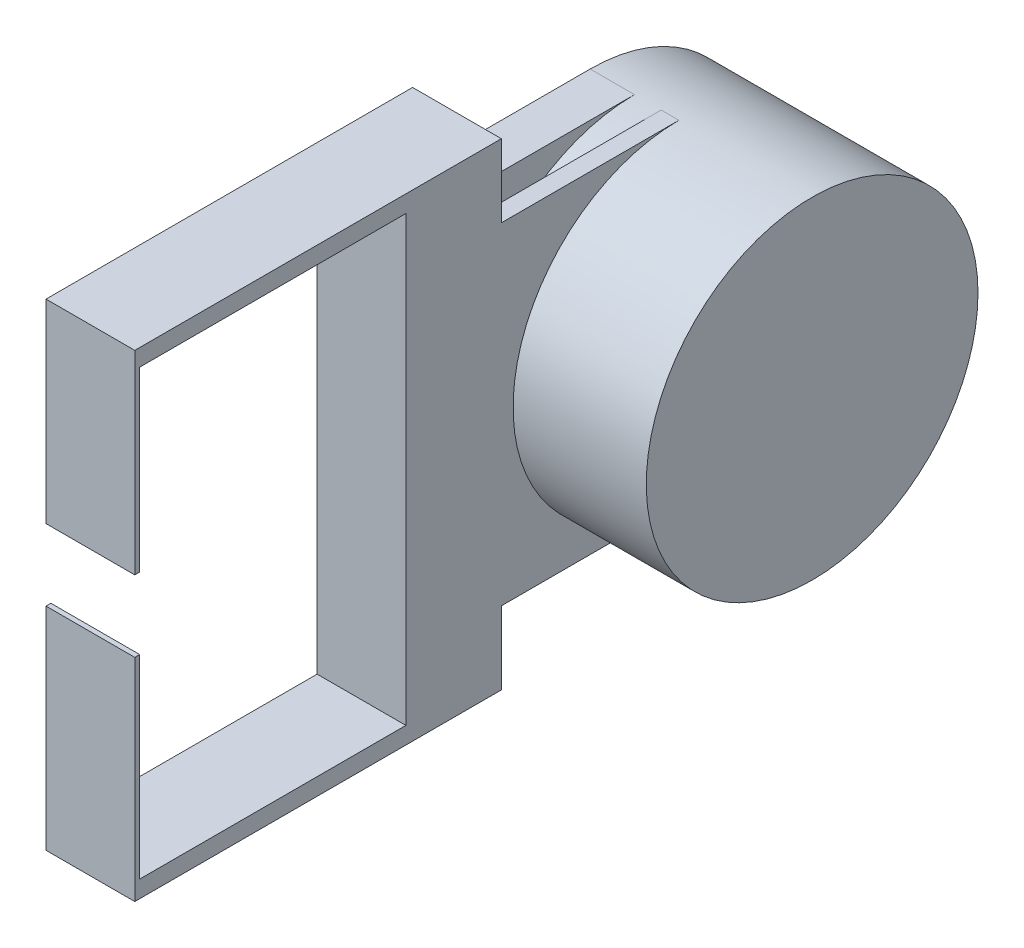
SolidWorks part; units mm, degrees
material "6061-T6 (SS)"
ref_plane "Front Plane" through (0, 0, 0) normal (1, 0, 0) x (0, 1, 0)
ref_plane "Top Plane" through (0, 0, 0) normal (0, 0, 1) x (0, 1, 0)
ref_plane "Right Plane" through (0, 0, 0) normal (0, 1, 0) x (-1, 0, 0)
sketch "Sketch1" plane through (0, 0, 0) normal (1, 0, 0) x (0, 1, 0)
  circle A0 centre (0, 0) radius 23.7249
  dimension "D1" = 47.4497
extrude "Boss-Extrude1" add sketch "Sketch1" along normal blind 31.75 contours A0
sketch "Sketch2" plane through (0, 0, 0) normal (0, 0, 1) x (0, 1, 0)
  line L0 (-23.7249, 0) -> (23.7249, 0)
  line L1 (-23.7249, 0) -> (-23.7249, -31.75) construction
  line L2 (23.7249, -31.75) -> (23.7249, 0) construction
  line L3 (-55, 0) -> (55, 0) construction
  line L4 (23.7249, 0) -> (23.7249, -6.35)
  line L5 (23.7249, -6.35) -> (-23.7249, -6.35)
  line L6 (-23.7249, -6.35) -> (-23.7249, 0)
  line L7 (23.7249, 0) -> (-23.7249, 0) construction
  dimension "D1" = 6.35
extrude "Boss-Extrude2" add sketch "Sketch2" along normal blind 25.4
sketch "Sketch3" plane through (0, 0, 25.4) normal (0, 0, 1) x (1, 0, 0)
  line L0 (0, -34.1414) -> (12.7, -34.1414)
  line L1 (0, 23.7249) -> (0, -23.7249) construction
  line L6 (0, -34.1414) -> (0, 34.1414)
  line L7 (0, 34.1414) -> (12.7, 34.1414)
  line L9 (12.7, 34.1414) -> (12.7, -34.1414)
  point P2 (0, 38.1)
  point P3 (0, 0)
  point P4 (10.2106, -34.1427)
  point P5 (0, 0)
  point P10 (12.7, -36.6742)
  point P11 (0, 0)
  point P12 (0, -38.1)
  point P16 (0, 0)
  point P17 (0, 0)
  dimension "D1" = 12.7
  dimension "D2" = 34.1414
  dimension "D3" = 34.1414
extrude "Boss-Extrude3" add sketch "Sketch3" along normal blind 13.6576
sketch "Sketch4" plane through (0, 0, 39.0576) normal (0, 0, 1) x (1, 0, 0)
  line L0 (0, 34.1414) -> (12.7, 34.1414)
  line L1 (12.7, 34.1414) -> (12.7, 31.7055)
  line L2 (12.7, -34.1414) -> (12.7, 34.1414) construction
  line L3 (12.7, 31.7055) -> (0, 31.7055)
  line L4 (0, 34.1414) -> (0, -34.1414) construction
  line L5 (0, 31.7055) -> (0, 34.1414)
  line L6 (0, -34.1414) -> (12.7, -34.1414)
  line L7 (12.7, -34.1414) -> (12.7, -31.7055)
  line L8 (12.7, -31.7055) -> (0, -31.7055)
  line L9 (0, -31.7055) -> (0, -34.1414)
  dimension "D1" = 2.4359
extrude "Boss-Extrude4" add sketch "Sketch4" along normal blind 38.0746
sketch "Sketch5" plane through (0, 0, 77.1322) normal (0, 0, 1) x (1, 0, 0)
  line L0 (0, 34.1414) -> (0, 6.3259)
  line L1 (0, 31.7055) -> (0, -31.7055) construction
  line L2 (0, 6.3259) -> (12.7, 6.3259)
  line L3 (12.7, -31.7055) -> (12.7, 31.7055) construction
  line L4 (12.7, 6.3259) -> (12.7, 34.1414)
  line L5 (12.7, 34.1414) -> (0, 34.1414)
  line L6 (0, -34.1414) -> (0, -3.89)
  line L7 (0, -3.89) -> (12.7, -3.89)
  line L8 (12.7, -3.89) -> (12.7, -34.1414)
  line L9 (0, -34.1414) -> (12.7, -34.1414) construction
  line L10 (12.7, -34.1414) -> (0, -34.1414)
  line L11 (12.7, -31.7055) -> (0, -31.7055) construction
  dimension "D1" = 27.8155
  dimension "D2" = 27.8155
extrude "Boss-Extrude5" add sketch "Sketch5" along normal blind 0.7036
sketch "Sketch9" plane through (0, 0, 25.4) normal (0, 0, -1) x (1, 0, 0)
  line L0 (12.7, 23.7249) -> (10.16, 23.7249)
  line L1 (31.75, 23.7249) -> (6.35, 23.7249) construction
  line L2 (12.7, 34.1414) -> (12.7, -34.1414) construction
  line L3 (10.16, 23.7249) -> (10.16, -23.7249)
  line L4 (6.35, -23.7249) -> (31.75, -23.7249) construction
  line L5 (10.16, -23.7249) -> (12.7, -23.7249)
  line L6 (12.7, -23.7249) -> (12.7, 23.7249)
  dimension "D1" = 2.54
extrude "Boss-Extrude8" add sketch "Sketch9" along normal up to surface (25.4 mm away) up to plane "Top Plane"
equation "\"deflmax\"= .005"
equation "\"modulus\"= 10000000"
equation "\"Smax\"= 40000"
equation "\"force\"= 800"
equation "\"l1\"= 1"
equation "\"SF\"= 4"
equation "\"d\" = \"SF\" * ( ( \"force\" * \"l1\" * 16 ) / ( \"Smax\" * pi ) ) ^ ( 1 / 3 )"
equation "\"t2\"= \"force\" / ( \"d\" * \"Smax\" )"
equation "\"l2\"= \"modulus\" * \"d\" * \"t2\" * \"deflmax\" / \"force\""
equation "\"t4\" = .5"
equation "\"l4\"= 1.499"
equation "\"w4\" = \"l4\" * \"force\" * \"SF\" / 2 / ( \"modulus\" * \"deflmax\" * \"t4\" )"
equation "\"l5\"= \"w4\" + .9992"
equation "\"w5\" = ( ( \"force\" * \"w4\" ^ 3 * 3 ) / ( \"modulus\" * \"t4\" * \"deflmax\" * 4 ) ) ^ ( 1 / 3 )"
equation "\"l3\"= .498 + 2 * .9992 + ( \"w4\" * 2 )"
equation "\"w3\"= ( ( \"force\" * \"l3\" ^ 3 ) / ( \"modulus\" * \"t4\" * \"deflmax\" * 4 ) ) ^ ( 1 / 3 )"
equation "\"a\"= .498"
equation "\"b\"= .9992"
